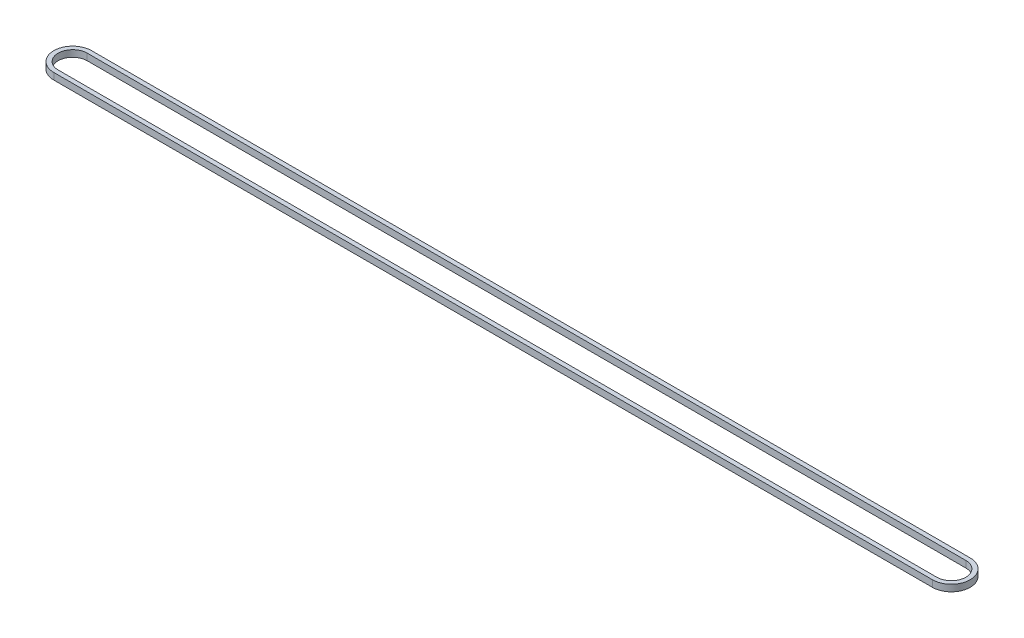
SolidWorks part; units mm, degrees
ref_plane "Front Plane" through (0, 0, 0) normal (0, 0, 1) x (1, 0, 0)
ref_plane "Top Plane" through (0, 0, 0) normal (0, 1, 0) x (1, 0, 0)
ref_plane "Right Plane" through (0, 0, 0) normal (1, 0, 0) x (0, 0, -1)
sketch "Sketch1" plane through (0, 0, 0) normal (0, 1, 0) x (1, 0, 0)
  line L0 (0, 25.4) -> (0, -25.4) construction
  line L1 (-1000, 0) -> (49000, 0) construction
  line L2 (0, 25.4) -> (1181.1, 25.4)
  line L3 (590.55, 25.4) -> (590.55, -25.4) construction
  line L4 (0, -25.4) -> (590.55, -25.4) construction
  line L5 (0, -25.4) -> (1181.1, -25.4)
  line L6 (0, 19.558) -> (1181.1, 19.558)
  line L7 (0, -19.558) -> (1181.1, -19.558)
  arc A0 (0, 25.4) -> (0, -25.4) centre (0, 0) ccw
  arc A1 (0, 19.558) -> (0, -19.558) centre (0, 0) ccw
  arc A2 (0, -25.4) -> (0, 25.4) centre (0, 0) ccw construction
  arc A3 (0, -19.558) -> (0, 19.558) centre (0, 0) ccw construction
  arc A4 (1181.1, 25.4) -> (1181.1, -25.4) centre (1181.1, 0) cw
  arc A5 (1181.1, 19.558) -> (1181.1, -19.558) centre (1181.1, 0) cw
  point P17 (0, 0)
  dimension "D1" = 50.8
  dimension "D2" = 5.842
  dimension "D3" = 590.55
extrude "Boss-Extrude1" add sketch "Sketch1" along normal blind 8.89
